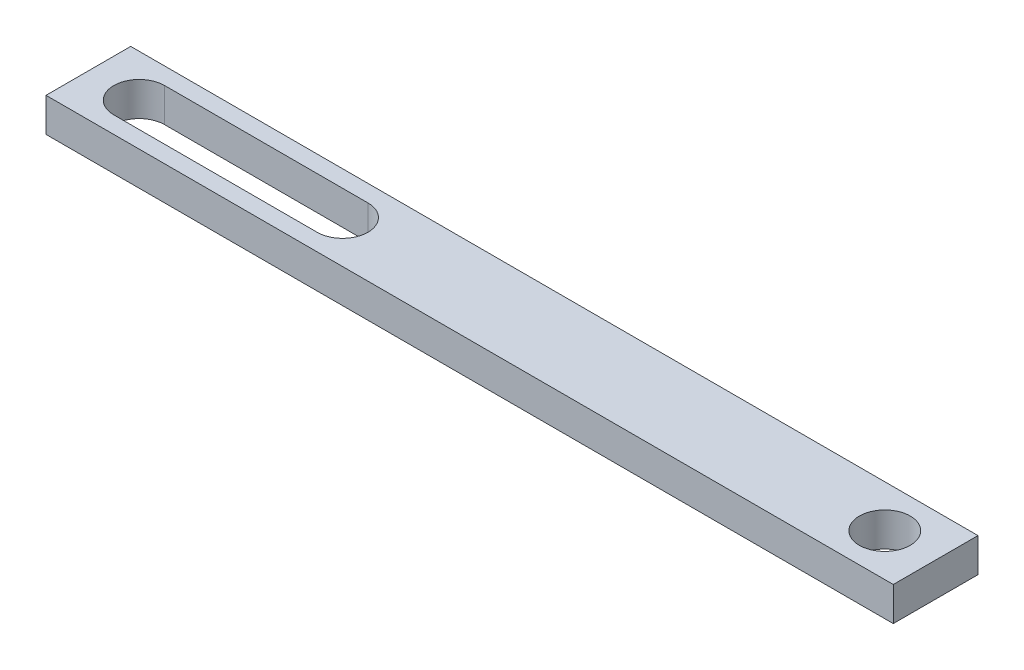
SolidWorks part; units mm, degrees
ref_plane "Front Plane" through (0, 0, 0) normal (0, 0, 1) x (1, 0, 0)
ref_plane "Top Plane" through (0, 0, 0) normal (0, 1, 0) x (1, 0, 0)
ref_plane "Right Plane" through (0, 0, 0) normal (1, 0, 0) x (0, 0, -1)
sketch "Sketch2" plane through (0, 0, 0) normal (0, 1, 0) x (1, 0, 0)
  line L0 (3, 4) -> (15, 4)
  line L1 (0, 0) -> (50, 0)
  line L2 (0, 0) -> (0, 5)
  line L3 (0, 5) -> (50, 5)
  line L4 (50, 0) -> (50, 5)
  line L5 (15, 1) -> (3, 1)
  arc A0 (3, 4) -> (3, 1) centre (3, 2.5) ccw
  arc A1 (15, 1) -> (15, 4) centre (15, 2.5) ccw
  circle A2 centre (47, 2.5) radius 1.5
  dimension "D1" = 3
  dimension "D4" = 3
  dimension "D7" = 3
  dimension "D2" = 50
  dimension "D3" = 5
  dimension "D5" = 2.5
  dimension "D6" = 15
  dimension "D8" = 3
  dimension "D9" = 2.5
extrude "Boss-Extrude1" add sketch "Sketch2" along normal blind 2
sketch "Sketch3" plane through (0, 2, 0) normal (0, 1, 0) x (1, 0, 0)
  line L0 (15, 4) -> (3, 4) construction
  line L1 (3, 1) -> (15, 1) construction
  line L2 (15, 4) -> (3, 4)
  line L3 (3, 1) -> (15, 1)
  line L4 (3, 2.5) -> (15, 2.5)
  arc A0 (15, 1) -> (15, 4) centre (15, 2.5) ccw construction
  arc A1 (3, 4) -> (3, 1) centre (3, 2.5) ccw construction
  arc A2 (15, 1) -> (15, 4) centre (15, 2.5) ccw
  arc A3 (3, 4) -> (3, 1) centre (3, 2.5) ccw
  circle A4 centre (47, 2.5) radius 1.5
  dimension "D1" = 3
